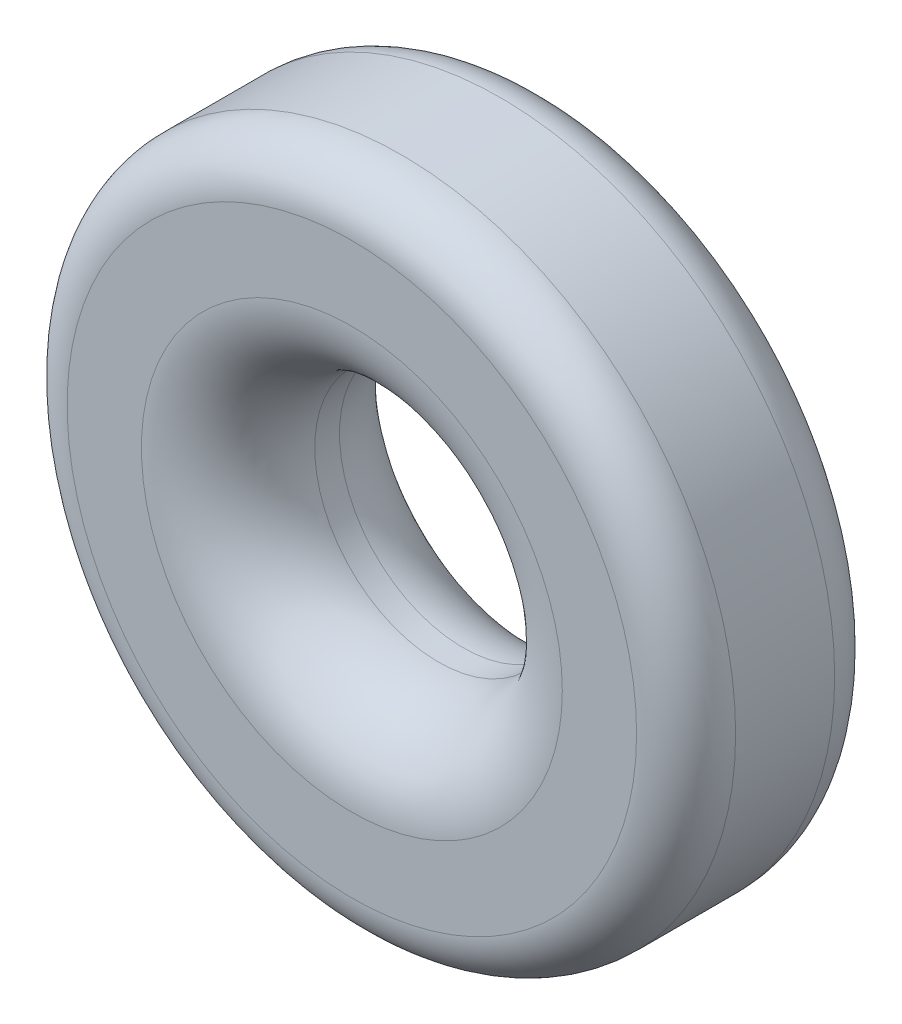
SolidWorks part; units mm, degrees
material "Резина"
ref_plane "Спереди" through (0, 0, 0) normal (0, 0, 1) x (1, 0, 0)
ref_plane "Сверху" through (0, 0, 0) normal (0, 1, 0) x (1, 0, 0)
ref_plane "Справа" through (0, 0, 0) normal (1, 0, 0) x (0, 0, -1)
sketch "Эскиз1" plane through (0, 0, 0) normal (0, 0, 1) x (1, 0, 0)
  circle A0 centre (0, 0) radius 135
  circle A1 centre (0, 0) radius 50
  dimension "D1" = 100
  dimension "D2" = 270
extrude "Вытянуть1" add sketch "Эскиз1" along normal blind 80
fillet "Скругление4" radius 20 1 edges at (135, 0, 0)
fillet "Скругление5" radius 20 1 edges at (135, 0, 80)
fillet "Скругление6" radius 35 1 edges at (50, 0, 0)
fillet "Скругление7" radius 35 1 edges at (50, 0, 80)
